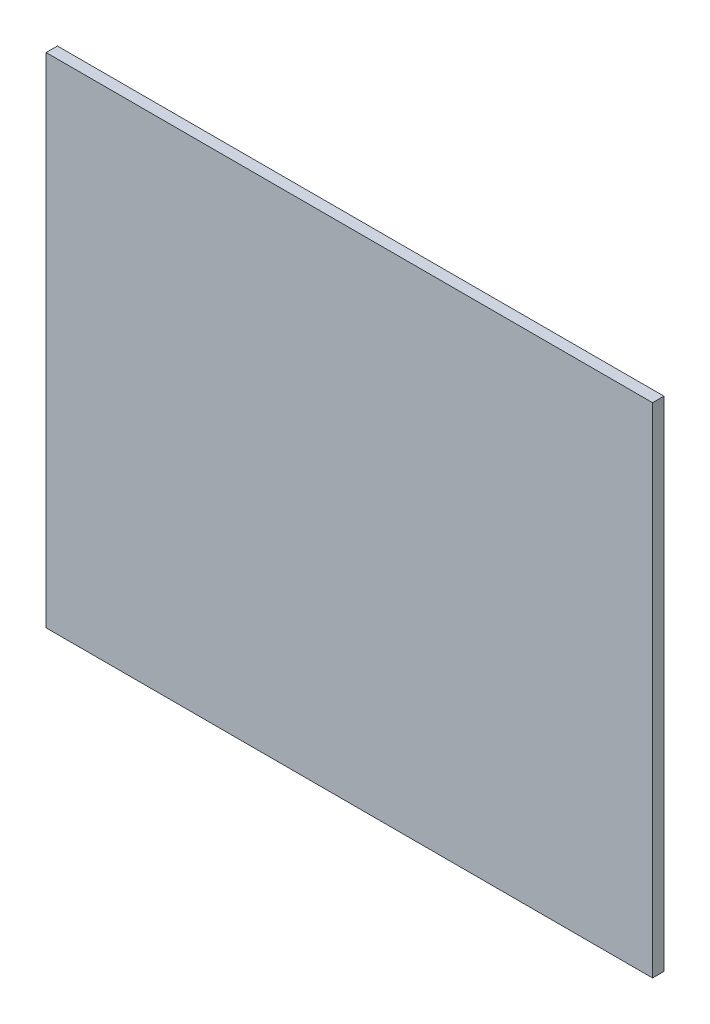
SolidWorks part; units mm, degrees
material "Teak"
ref_plane "Front Plane" through (0, 0, 0) normal (0, 0, 1) x (1, 0, 0)
ref_plane "Top Plane" through (0, 0, 0) normal (0, 1, 0) x (1, 0, 0)
ref_plane "Right Plane" through (0, 0, 0) normal (1, 0, 0) x (0, 0, -1)
sketch "Sketch1" plane through (0, 0, 0) normal (0, 0, 1) x (1, 0, 0)
  line L1 (0, 0) -> (964, 0)
  line L2 (0, 0) -> (0, 792)
  line L3 (0, 792) -> (964, 792)
  line L4 (964, 0) -> (964, 792)
  dimension "D1" = 964
  dimension "D2" = 792
extrude "Boss-Extrude1" add sketch "Sketch1" along normal blind 18
